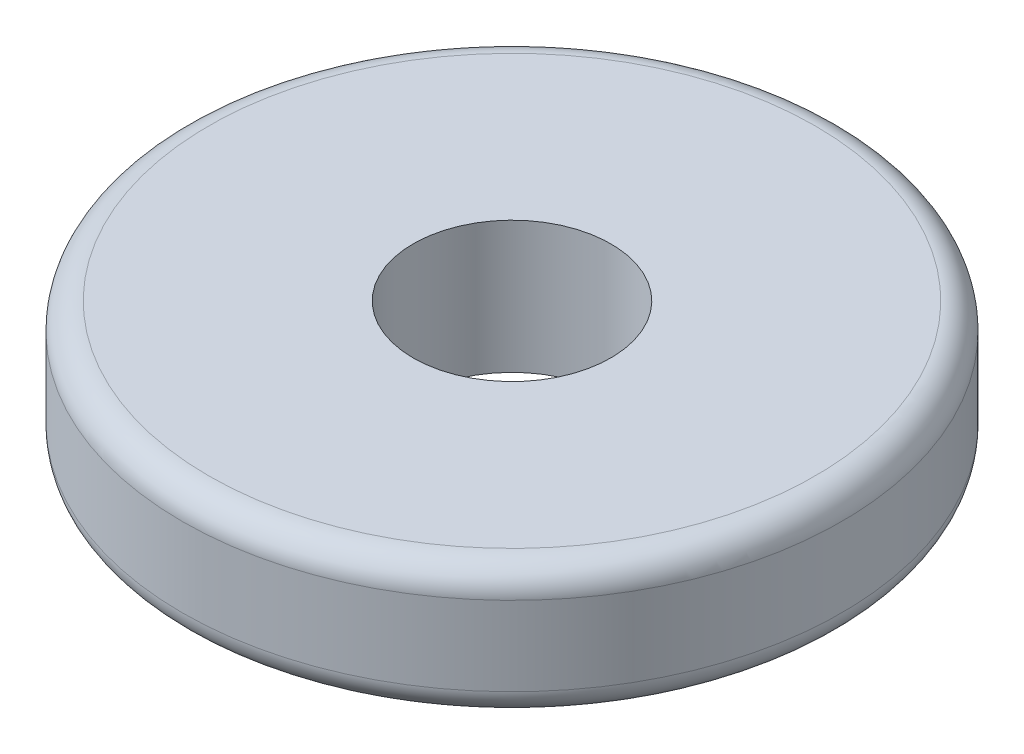
SolidWorks part; units mm, degrees
ref_plane "Front Plane" through (0, 0, 0) normal (0, 0, 1) x (1, 0, 0)
ref_plane "Top Plane" through (0, 0, 0) normal (0, 1, 0) x (1, 0, 0)
ref_plane "Right Plane" through (0, 0, 0) normal (1, 0, 0) x (0, 0, -1)
sketch "Sketch1" plane through (0, 0, 0) normal (0, 1, 0) x (1, 0, 0)
  circle A0 centre (0, 0) radius 31.75
  circle A2 centre (0, 0) radius 9.525
  dimension "D1" = 63.5
  dimension "D2" = 19.05
extrude "Boss-Extrude1" add sketch "Sketch1" along normal blind 12.7
fillet "Fillet1" radius 2.54 2 edges at (0, 0, 31.75) (0, 12.7, 31.75)
